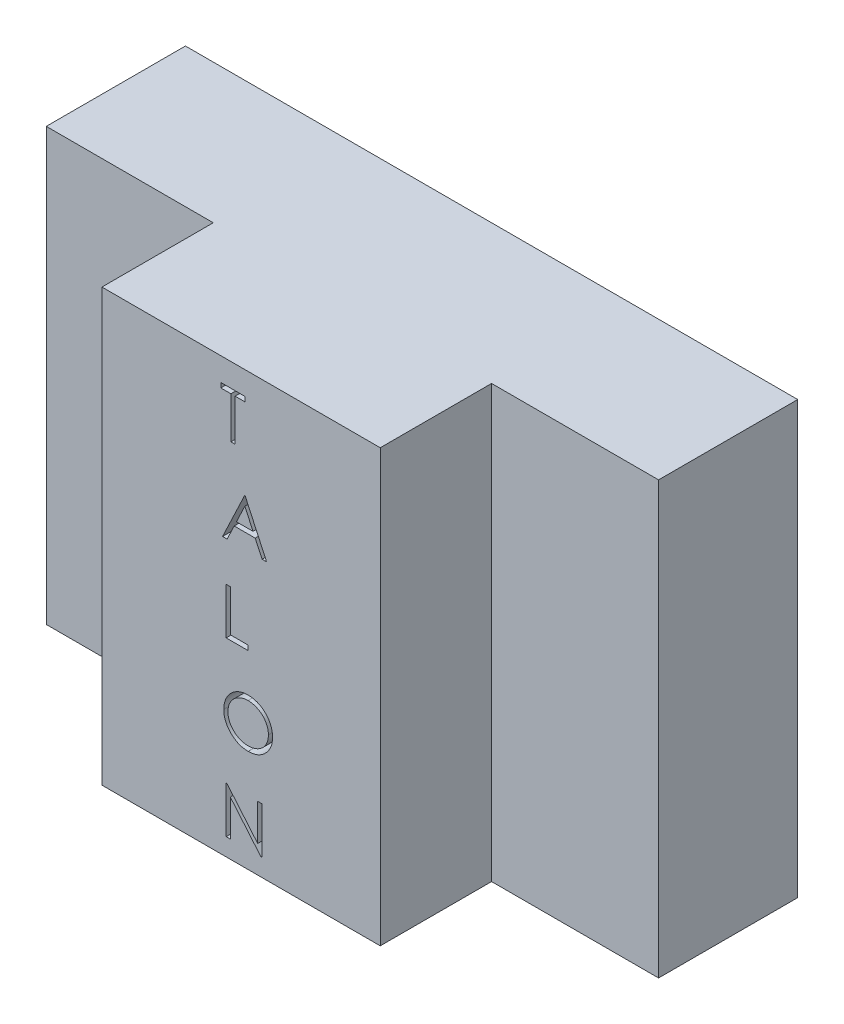
SolidWorks part; units mm, degrees
ref_plane "Front Plane" through (0, 0, 0) normal (0, 0, 1) x (1, 0, 0)
ref_plane "Top Plane" through (0, 0, 0) normal (0, 1, 0) x (1, 0, 0)
ref_plane "Right Plane" through (0, 0, 0) normal (1, 0, 0) x (0, 0, -1)
sketch "Sketch2" plane through (0, 0, 0) normal (0, 0, 1) x (1, 0, 0)
  line L1 (0, 0) -> (69.85, 0)
  line L2 (0, 0) -> (0, 49.2125)
  line L3 (0, 49.2125) -> (69.85, 49.2125)
  line L4 (69.85, 0) -> (69.85, 49.2125)
  dimension "D1" = 69.85
  dimension "D2" = 49.2125
extrude "Boss-Extrude1" add sketch "Sketch2" along normal blind 28.575
sketch "Sketch3" plane through (0, 0, 28.575) normal (0, 0, 1) x (1, 0, 0)
  line L0 (0, 0) -> (69.85, 0) construction
  line L1 (0, 49.2125) -> (19.05, 49.2125)
  line L2 (0, 49.2125) -> (0, 0)
  line L3 (0, 0) -> (19.05, 0)
  line L4 (19.05, 49.2125) -> (19.05, 0)
  line L6 (69.85, 49.2125) -> (50.8, 49.2125)
  line L7 (69.85, 49.2125) -> (69.85, 0)
  line L8 (69.85, 0) -> (50.8, 0)
  line L9 (50.8, 49.2125) -> (50.8, 0)
  dimension "D1" = 19.05
  dimension "D2" = 19.05
extrude "Cut-Extrude1" cut sketch "Sketch3" against normal blind 12.7
sketch "Sketch4" plane through (0, 0, 28.575) normal (0, 0, 1) x (1, 0, 0)
  line L1 (50.8, 49.2125) -> (19.05, 49.2125) construction
  line L3 (19.05, 0) -> (19.05, 49.2125) construction
  text T0 "T\r\nA\r\nL\r\nO\r\nN" font "Century Gothic" height in points 20
  dimension "D1" = 7.9375
  dimension "D2" = 13.4937
extrude "Cut-Extrude3" cut sketch "Sketch4" against normal through all
